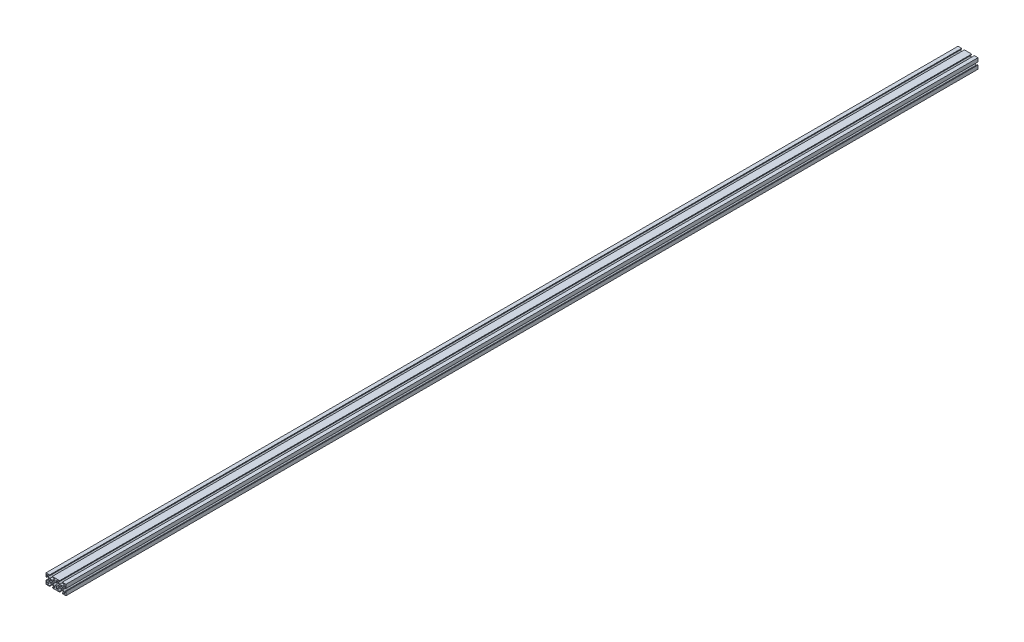
SolidWorks part; units mm, degrees
material "6063-T5"
ref_plane "Front Plane" through (0, 0, 0) normal (0, 0, 1) x (1, 0, 0)
ref_plane "Top Plane" through (0, 0, 0) normal (0, 1, 0) x (1, 0, 0)
ref_plane "Right Plane" through (0, 0, 0) normal (1, 0, 0) x (0, 0, -1)
sketch "Sketch1" plane through (0, 0, 0) normal (0, 0, 1) x (1, 0, 0)
  line L0 (0, 20) -> (20, 0) construction
  line L1 (0, 0) -> (20, 0) construction
  line L2 (0, 0) -> (0, 20) construction
  line L3 (0, 20) -> (20, 20) construction
  line L4 (20, 0) -> (20, 20) construction
  line L5 (20, 20) -> (0, 0) construction
  line L6 (18.5, 1.5) -> (18.5, 0) construction
  line L7 (1.5, 1.5) -> (18.5, 1.5) construction
  line L8 (1.5, 1.5) -> (1.5, 18.5) construction
  line L9 (1.5, 18.5) -> (18.5, 18.5) construction
  line L10 (18.5, 1.5) -> (18.5, 18.5) construction
  line L11 (18.5, 1.5) -> (20, 1.5) construction
  line L12 (6.345, 12.5943) -> (1.5, 17.4393)
  line L13 (13.655, 6.345) -> (6.345, 6.345) construction
  line L14 (13.655, 6.345) -> (13.655, 13.655) construction
  line L15 (13.655, 13.655) -> (6.345, 13.655) construction
  line L16 (6.345, 6.345) -> (6.345, 13.655) construction
  line L17 (7.4057, 13.655) -> (2.5607, 18.5)
  line L18 (2.5607, 18.5) -> (2.0303, 17.9697) construction
  line L19 (2.0303, 17.9697) -> (1.5, 17.4393) construction
  line L20 (6.345, 7.4057) -> (6.345, 12.5943)
  line L21 (12.5943, 13.655) -> (17.4393, 18.5)
  line L22 (17.4393, 18.5) -> (17.9697, 17.9697) construction
  line L23 (17.9697, 17.9697) -> (18.5, 17.4393) construction
  line L24 (18.5, 17.4393) -> (13.655, 12.5943)
  line L25 (13.655, 7.4057) -> (18.5, 2.5607)
  line L26 (18.5, 2.5607) -> (17.9697, 2.0303) construction
  line L27 (17.4393, 1.5) -> (12.5943, 6.345)
  line L28 (7.4057, 6.345) -> (2.5607, 1.5)
  line L29 (17.9697, 2.0303) -> (17.4393, 1.5) construction
  line L30 (1.5, 2.5607) -> (6.345, 7.4057)
  line L31 (2.5607, 1.5) -> (2.0303, 2.0303) construction
  line L32 (2.0303, 2.0303) -> (1.5, 2.5607) construction
  line L33 (7.4057, 13.655) -> (12.5943, 13.655)
  line L34 (13.655, 12.5943) -> (13.655, 7.4057)
  line L36 (12.5943, 6.345) -> (7.4057, 6.345)
  line L37 (0, 10) -> (1.5, 10) construction
  line L38 (0.75, 12.63) -> (0.75, 10) construction
  line L39 (0.75, 10) -> (0.75, 7.37) construction
  line L40 (1.5, 12.63) -> (0, 12.63)
  line L41 (1.5, 7.37) -> (0, 7.37)
  line L42 (10, 1.5) -> (10, 0) construction
  line L43 (10, 0.75) -> (12.63, 0.75) construction
  line L44 (10, 0.75) -> (7.37, 0.75) construction
  line L45 (12.63, 0) -> (12.63, 1.5)
  line L46 (7.37, 1.5) -> (7.37, 0)
  line L47 (18.5, 12.63) -> (20, 12.63)
  line L48 (18.5, 7.37) -> (20, 7.37)
  line L49 (7.37, 20) -> (7.37, 18.5)
  line L50 (12.63, 20) -> (12.63, 18.5)
  line L51 (2.5607, 1.5) -> (7.37, 1.5)
  line L52 (12.63, 1.5) -> (17.4393, 1.5)
  line L53 (18.5, 7.37) -> (18.5, 2.5607)
  line L54 (18.5, 12.63) -> (18.5, 17.4393)
  line L55 (17.4393, 18.5) -> (12.63, 18.5)
  line L56 (7.37, 18.5) -> (2.5607, 18.5)
  line L57 (1.5, 17.4393) -> (1.5, 12.63)
  line L58 (1.5, 7.37) -> (1.5, 2.5607)
  line L59 (7.37, 0) -> (0, 0)
  line L60 (0, 0) -> (0, 7.37)
  line L61 (0, 12.63) -> (0, 20)
  line L62 (0, 20) -> (7.37, 20)
  line L63 (12.63, 20) -> (20, 20)
  line L64 (20, 20) -> (20, 12.63)
  line L65 (20, 7.37) -> (20, 0)
  line L66 (20, 0) -> (12.63, 0)
  circle A0 centre (10, 10) radius 2.095
  dimension "D2" = 4.19
  dimension "D6" = 5.26
  dimension "D1" = 20
  dimension "D3" = 1.5
  dimension "D4" = 3.655
  dimension "D5" = 1.5
extrude "Boss-Extrude1" add sketch "Sketch1" along normal blind 1830
pattern_linear "LPattern1" count 2 spacing 20 along (1, 0, 0) of "Boss-Extrude1"
